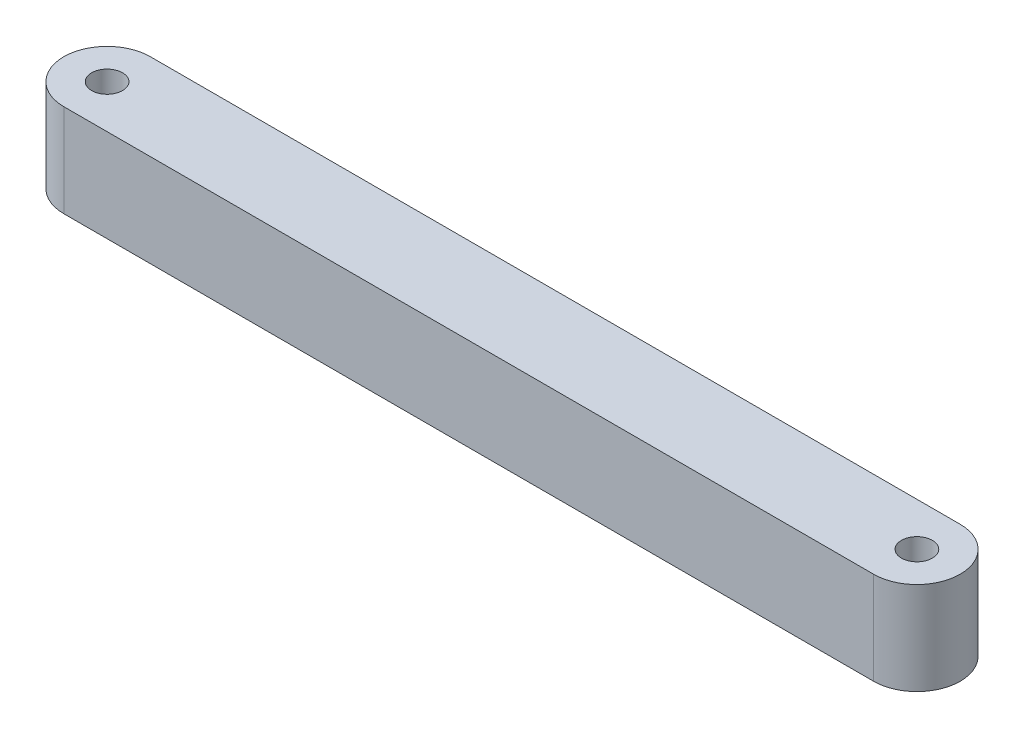
SolidWorks part; units mm, degrees
ref_plane "Front Plane" through (0, 0, 0) normal (0, 0, 1) x (1, 0, 0)
ref_plane "Top Plane" through (0, 0, 0) normal (0, 1, 0) x (1, 0, 0)
ref_plane "Right Plane" through (0, 0, 0) normal (1, 0, 0) x (0, 0, -1)
sketch "Sketch1" plane through (0, 0, 0) normal (0, 1, 0) x (1, 0, 0)
  line L0 (-131, 7) -> (0, 7)
  line L1 (0, -7) -> (-131, -7)
  line L2 (-131, -7) -> (-55.1185, -7)
  circle A0 centre (0, 0) radius 2.5
  circle A1 centre (-131, 0) radius 2.5
  circle A2 centre (0, 0) radius 7
  circle A3 centre (-131, 0) radius 7
  dimension "D1" = 5
  dimension "D2" = 5
  dimension "D3" = 14
  dimension "D4" = 14
  dimension "D5" = 131
extrude "Boss-Extrude1" add sketch "Sketch1" along normal blind 15 contours A3 L1 A2 L0 | A3 A1 | A2 A0
